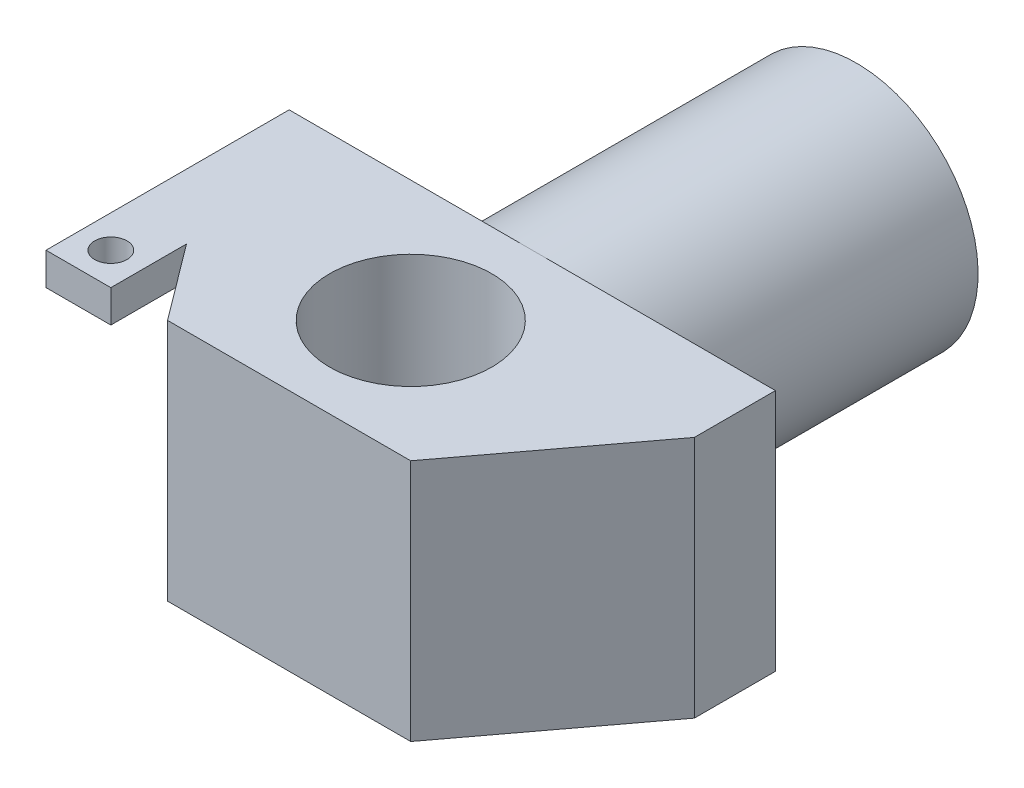
SolidWorks part; units mm, degrees
ref_plane "Front Plane" through (0, 0, 0) normal (0, 0, 1) x (1, 0, 0)
ref_plane "Top Plane" through (0, 0, 0) normal (0, 1, 0) x (1, 0, 0)
ref_plane "Right Plane" through (0, 0, 0) normal (1, 0, 0) x (0, 0, -1)
sketch "Sketch1" plane through (0, 0, 0) normal (0, 1, 0) x (1, 0, 0)
  line L0 (-43.1528, -30.6721) -> (-35.6528, -30.6721)
  line L1 (-35.6528, -30.6721) -> (-31.9028, -25.6721)
  line L2 (-31.9028, -25.6721) -> (-31.9028, -23.1721)
  line L3 (-31.9028, -23.1721) -> (-46.9028, -23.1721)
  line L4 (-46.9028, -23.1721) -> (-46.9028, -25.6721)
  line L5 (-46.9028, -25.6721) -> (-43.1528, -30.6721)
  circle A0 centre (-39.4028, -26.9221) radius 2.5
  dimension "D1" = 5
  dimension "D5" = 3.75
  dimension "D6" = 3.75
  dimension "D2" = 5
  dimension "D3" = 5
  dimension "D4" = 7.5
  dimension "D7" = 15
  dimension "D8" = 3.75
  dimension "D9" = 2.5
  dimension "D10" = 2.5
extrude "Boss-Extrude1" add sketch "Sketch1" along normal blind 7.5
sketch "Sketch2" plane through (0, 0, 23.1721) normal (0, 0, -1) x (-1, 0, 0)
  line L0 (31.9028, 0) -> (46.9028, 0) construction
  line L1 (31.9028, 7.5) -> (31.9028, 0) construction
  circle A0 centre (39.4028, 3.75) radius 3.75
  dimension "D1" = 7.5
  dimension "D2" = 3.75
  dimension "D3" = 7.5
extrude "Boss-Extrude2" add sketch "Sketch2" along normal blind 10
sketch "Sketch3" plane through (0, 0, 23.1721) normal (0, 0, -1) x (-1, 0, 0)
  line L1 (46.9028, 7.5) -> (44.9028, 7.5)
  line L2 (46.9028, 7.5) -> (46.9028, 6.5)
  line L3 (46.9028, 6.5) -> (44.9028, 6.5)
  line L4 (44.9028, 7.5) -> (44.9028, 6.5)
  dimension "D1" = 1
  dimension "D2" = 2
extrude "Boss-Extrude3" add sketch "Sketch3" against normal blind 7.5
sketch "Sketch4" plane through (0, 7.5, 0) normal (0, 1, 0) x (1, 0, 0)
  line L0 (-46.9028, -30.6721) -> (-44.9028, -30.6721) construction
  circle A0 centre (-45.9028, -29.6721) radius 0.5
  point P2 (-45.9028, -30.6721)
  point P5 (-45.9028, -30.6721)
  dimension "D1" = 1
  dimension "D2" = 1
  dimension "D3" = 0
extrude "Cut-Extrude1" cut sketch "Sketch4" against normal blind 1
